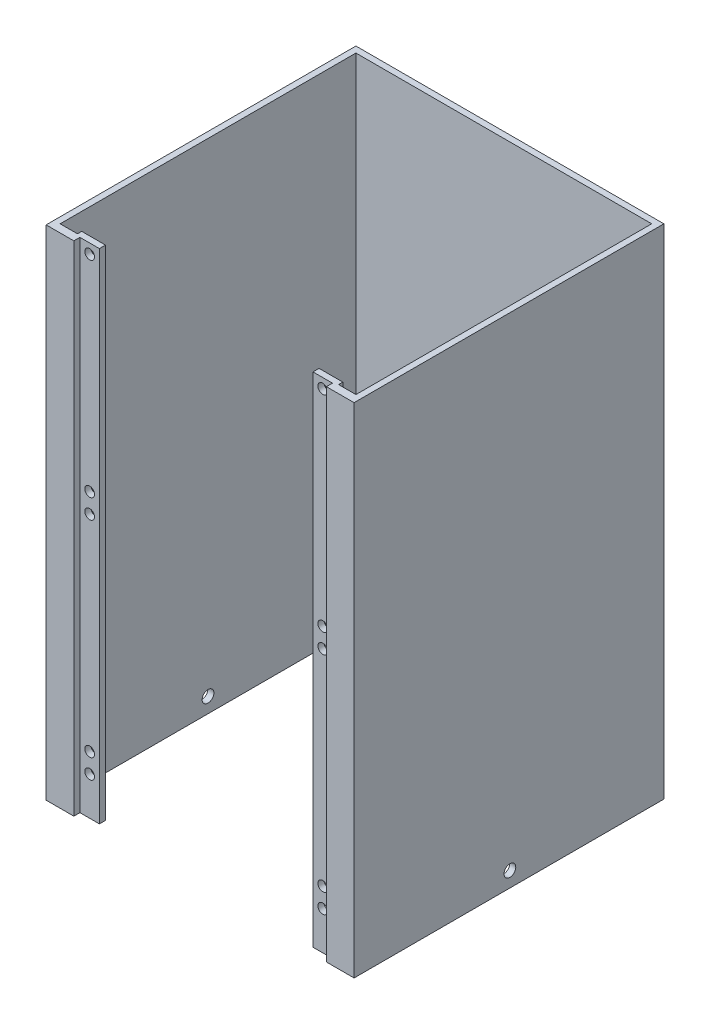
SolidWorks part; units mm, degrees
ref_plane "Front Plane" through (0, 0, 0) normal (0, 0, 1) x (1, 0, 0)
ref_plane "Top Plane" through (0, 0, 0) normal (0, 1, 0) x (1, 0, 0)
ref_plane "Right Plane" through (0, 0, 0) normal (1, 0, 0) x (0, 0, -1)
sketch "Sketch1" plane through (0, 0, 0) normal (0, 1, 0) x (1, 0, 0)
  line L0 (0, -0.603) -> (0, 101.206)
  line L1 (0, 101.206) -> (101.206, 101.206)
  line L2 (101.206, 101.206) -> (101.206, -0.6)
  line L3 (101.206, -0.6) -> (91.5, -0.6)
  line L4 (91.5, -0.6) -> (91.5, 1.4)
  line L5 (91.5, 1.4) -> (85.703, 1.4)
  line L6 (85.703, 1.4) -> (85.703, 3.4)
  line L7 (85.703, 3.4) -> (93.5, 3.4)
  line L8 (93.5, 3.4) -> (93.5, 2)
  line L9 (93.5, 2) -> (99.206, 2)
  line L10 (99.206, 2) -> (99.206, 99.206)
  line L11 (99.206, 99.206) -> (2, 99.206)
  line L12 (2, 99.206) -> (2, 2)
  line L13 (2, 2) -> (7.706, 2)
  line L14 (7.706, 2) -> (7.706, 3.397)
  line L15 (7.706, 3.397) -> (15.503, 3.397)
  line L16 (15.503, 3.397) -> (15.503, 1.397)
  line L17 (15.503, 1.397) -> (9.706, 1.397)
  line L18 (9.706, 1.397) -> (9.706, -0.603)
  line L19 (9.706, -0.603) -> (0, -0.603)
  dimension "D1" = 90
  dimension "D2" = 2
  dimension "D3" = 2
  dimension "D4" = 2
  dimension "D5" = 2
  dimension "D6" = 2
  dimension "D7" = 9.706
  dimension "D8" = 2
  dimension "D9" = 2
  dimension "D10" = 9.706
  dimension "D11" = 2
extrude "Boss-Extrude1" add sketch "Sketch1" along normal blind 327.5
sketch "Sketch2" plane through (0, 0, -1.397) normal (0, 0, 1) x (1, 0, 0)
  line L0 (9.706, 327.5) -> (15.503, 327.5) construction
  line L1 (15.503, 327.5) -> (15.503, 0) construction
  line L2 (85.703, 327.5) -> (85.703, 0) construction
  line L3 (85.703, 327.5) -> (91.5, 327.5) construction
  line L4 (9.706, 0) -> (15.503, 0) construction
  circle A0 centre (12.303, 314.9) radius 1.6
  circle A1 centre (12.303, 308.5) radius 1.6
  circle A2 centre (88.903, 314.9) radius 1.6
  circle A3 centre (88.903, 308.5) radius 1.6
  circle A4 centre (12.303, 240.925) radius 1.6
  circle A5 centre (12.303, 234.525) radius 1.6
  circle A6 centre (88.903, 240.925) radius 1.6
  circle A7 centre (88.903, 234.525) radius 1.6
  circle A8 centre (12.303, 166.95) radius 1.6
  circle A9 centre (12.303, 160.55) radius 1.6
  circle A10 centre (88.903, 166.95) radius 1.6
  circle A11 centre (88.903, 160.55) radius 1.6
  circle A12 centre (12.303, 92.975) radius 1.6
  circle A13 centre (12.303, 86.575) radius 1.6
  circle A14 centre (88.903, 92.975) radius 1.6
  circle A15 centre (88.903, 86.575) radius 1.6
  circle A16 centre (12.303, 19) radius 1.6
  circle A17 centre (12.303, 12.6) radius 1.6
  circle A18 centre (88.903, 19) radius 1.6
  circle A19 centre (88.903, 12.6) radius 1.6
  dimension "D1" = 3.2
  dimension "D2" = 3.2
  dimension "D3" = 12.6
  dimension "D4" = 6.4
  dimension "D5" = 3.2
  dimension "D6" = 3.2
  dimension "D8" = 3.2
  dimension "D9" = 3.2
  dimension "D10" = 12.6
  dimension "D12" = 12.6
  dimension "D7" = 2
  dimension "D11" = 5
extrude "Cut-Extrude2" cut sketch "Sketch2" against normal blind 10
sketch "Sketch3" plane through (101.206, 0, 0) normal (1, 0, 0) x (0, 0, -1)
  line L0 (-0.6, 327.5) -> (101.206, 327.5) construction
  line L3 (-0.6, 0) -> (101.206, 0) construction
  line L4 (2, 327.5) -> (2, 0) construction
  line L5 (99.206, 327.5) -> (99.206, 0) construction
  circle A0 centre (50.603, 322.524) radius 1.93
  circle A1 centre (50.603, 4.976) radius 1.93
  dimension "D1" = 3.86
  dimension "D7" = 3.86
  dimension "D2" = 4.976
  dimension "D3" = 48.603
  dimension "D4" = 48.603
  dimension "D5" = 48.603
  dimension "D6" = 4.976
  dimension "D8" = 48.603
extrude "Cut-Extrude3" cut sketch "Sketch3" against normal blind 102
sketch "Sketch4" plane through (0, 0, -101.206) normal (0, 0, -1) x (-1, 0, 0)
  line L0 (-101.206, 327.5) -> (0, 327.5) construction
  line L2 (-101.206, 0) -> (0, 0) construction
  line L3 (-2, 327.5) -> (-2, 0) construction
  line L4 (-99.206, 327.5) -> (-99.206, 0) construction
  circle A0 centre (-50.603, 322.524) radius 1.93
  circle A1 centre (-50.603, 4.976) radius 1.93
  dimension "D1" = 3.86
  dimension "D2" = 3.86
  dimension "D3" = 4.976
  dimension "D4" = 48.603
  dimension "D5" = 4.976
  dimension "D6" = 48.603
  dimension "D7" = 48.603
  dimension "D8" = 48.603
extrude "Cut-Extrude4" cut sketch "Sketch4" against normal blind 10
sketch "Sketch5" plane through (0, 0, 0) normal (-1, 0, 0) x (0, 0, 1)
  line L0 (-101.206, 327.5) -> (-101.206, 0) construction
  line L1 (15.5465, 329.4114) -> (-101.206, 329.4114)
  line L2 (15.5465, 329.4114) -> (15.5465, 163.75)
  line L3 (15.5465, 163.75) -> (-101.206, 163.75)
  line L4 (-101.206, 329.4114) -> (-101.206, 163.75)
extrude "Cut-Extrude5" cut sketch "Sketch5" against normal blind 191
sketch "Sketch6" plane through (0, 163.75, 0) normal (0, 1, 0) x (1, 0, 0)
  line L0 (9.706, -0.603) -> (0, -0.603) construction
  line L1 (9.103, -0.603) -> (92.103, -0.603)
  line L2 (9.103, -0.603) -> (9.103, 1.4)
  line L3 (9.103, 1.4) -> (92.103, 1.4)
  line L4 (92.103, -0.603) -> (92.103, 1.4)
  line L9 (0, 101.206) -> (0, -0.603) construction
  dimension "D1" = 83
  dimension "D2" = 9.103
extrude "Cut-Extrude6" cut sketch "Sketch6" against normal blind 203
